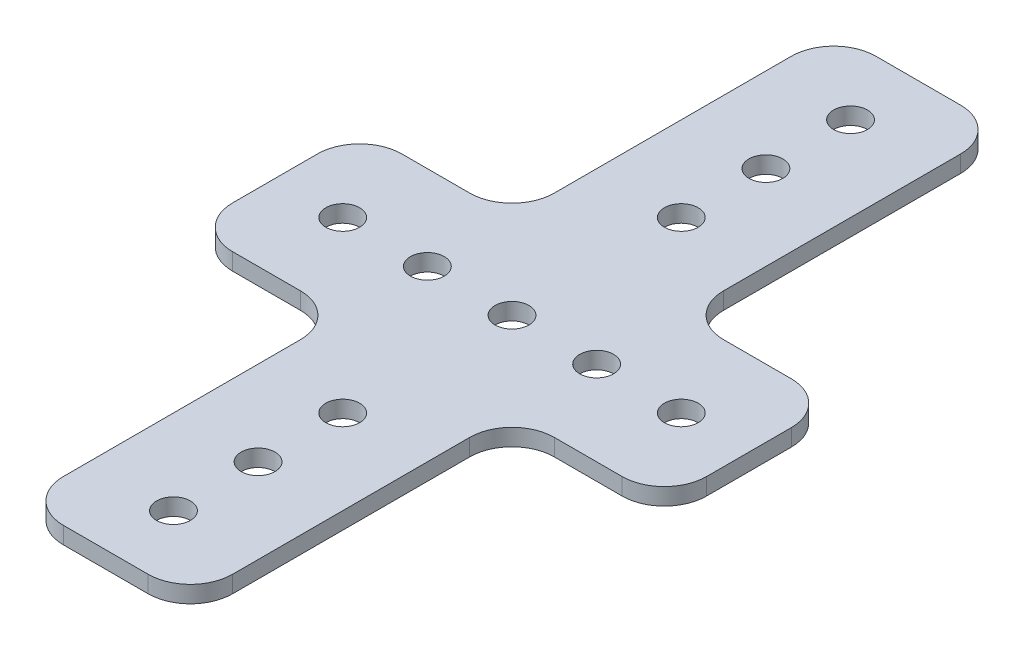
SolidWorks part; units mm, degrees
ref_plane "前基準面" through (0, 0, 0) normal (0, 0, 1) x (1, 0, 0)
ref_plane "上基準面" through (0, 0, 0) normal (0, 1, 0) x (1, 0, 0)
ref_plane "右基準面" through (0, 0, 0) normal (1, 0, 0) x (0, 0, -1)
sketch "草圖1" plane through (0, 0, 0) normal (0, 1, 0) x (1, 0, 0)
  line L1 (0, -8) -> (0, -28) construction
  line L2 (0, -28) -> (0, -48) construction
  line L3 (0, -48) -> (0, -68) construction
  line L4 (0, -68) -> (0, -88) construction
  line L5 (0, -88) -> (0, -96) construction
  line L6 (-28, -48) -> (-20, -48) construction
  line L7 (-28, -38) -> (-28, -58)
  line L8 (-20, -48) -> (0, -48) construction
  line L9 (0, -48) -> (20, -48) construction
  line L10 (28, -58) -> (28, -38)
  line L11 (20, -48) -> (28, -48) construction
  line L12 (-10, -96) -> (10, -96)
  line L13 (-28, -38) -> (-10, -38)
  line L14 (-10, -38) -> (-10, 0)
  line L15 (10, 0) -> (10, -38)
  line L16 (10, -38) -> (28, -38)
  line L17 (28, -58) -> (10, -58)
  line L18 (10, -58) -> (10, -96)
  line L19 (-10, -96) -> (-10, -58)
  line L20 (-10, -58) -> (-28, -58)
  line L21 (0, -8) -> (0, 0) construction
  line L22 (-10, 0) -> (10, 0)
  point P14 (-28, -48)
  point P18 (28, -48)
  point P21 (0, -96)
  point P30 (0, 0)
  dimension "D1" = 8
  dimension "D2" = 20
  dimension "D3" = 20
extrude "填料-伸長1" add sketch "草圖1" against normal blind 2
hole_wizard "Ø4.0 (4) 直徑孔1" positions "草圖2" profile "草圖3" hole size "Ø4.0" standard "ISO" end condition through all
sketch "草圖2" plane through (0, 0, 0) normal (0, 1, 0) x (1, 0, 0)
  point P0 (0, -28)
  point P3 (0, -48)
  point P6 (0, -68)
  point P9 (0, -88)
  point P12 (-20, -48)
  point P15 (20, -48)
  point P19 (0, -8)
sketch "草圖3" plane through (0, 0, 28) normal (1, 0, 0) x (0, 0, 1)
  line L0 (0, 0) -> (0, 2)
  line L1 (0, 2) -> (2, 2)
  line L2 (2, 2) -> (2, 0)
  line L5 (2, 0) -> (0, 0)
  line L11 (0, -6.35) -> (0, 107.95) construction
  dimension "貫穿孔直徑" = 4
  dimension "貫穿孔深度" = 2
hole_wizard "Ø4.0 (4) 直徑孔2" positions "草圖4" profile "草圖5" hole size "Ø4.0" standard "ISO" end condition through all
sketch "草圖4" plane through (0, 0, 0) normal (0, 1, 0) x (1, 0, 0)
  line L0 (0, -68) -> (0, -88) construction
  line L2 (0, -48) -> (20, -48) construction
  line L3 (-20, -48) -> (0, -48) construction
  line L5 (0, -8) -> (0, -28) construction
  point P0 (0, -18)
  point P4 (10, -48)
  point P6 (-10, -48)
  point P10 (0, -78)
sketch "草圖5" plane through (0, 0, 18) normal (1, 0, 0) x (0, 0, 1)
  line L0 (0, 0) -> (0, 2)
  line L1 (0, 2) -> (2, 2)
  line L2 (2, 2) -> (2, 0)
  line L5 (2, 0) -> (0, 0)
  line L11 (0, -6.35) -> (0, 107.95) construction
  dimension "貫穿孔直徑" = 4
  dimension "貫穿孔深度" = 2
fillet "圓角1" radius 5 4 edges at (-10, -1, 38) (-10, -1, 58) (10, -1, 58) (10, -1, 38)
fillet "圓角2" radius 5 8 edges at (-28, -1, 58) (-28, -1, 38) (-10, -1, 0) (10, -1, 0) (28, -1, 38) (28, -1, 58) (10, -1, 96) (-10, -1, 96)
